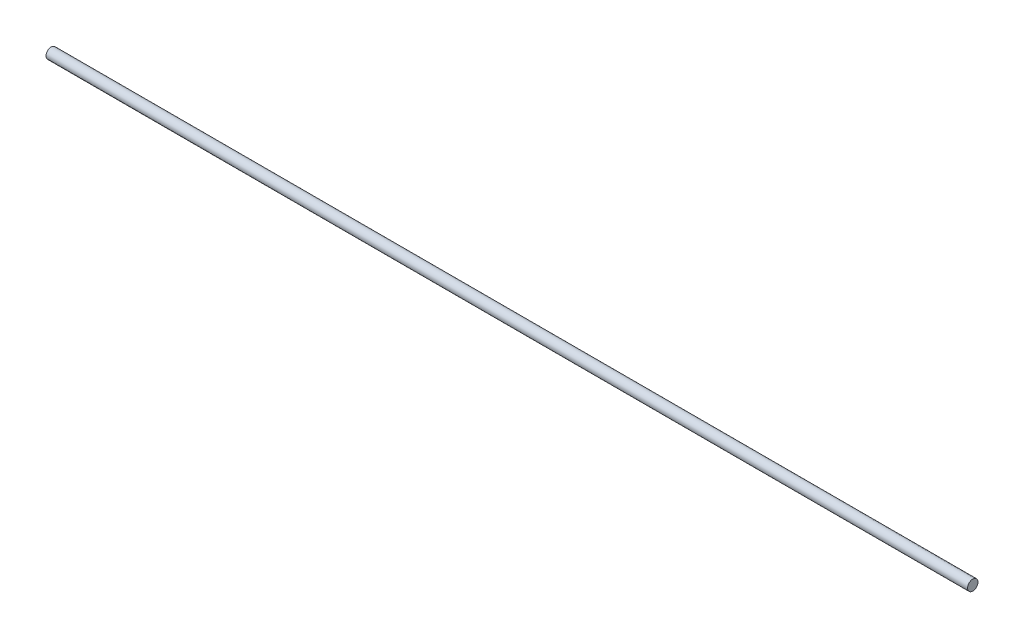
SolidWorks part; units mm, degrees
material "6061-T6 (SS)"
ref_plane "Front Plane" through (0, 0, 0) normal (0, 0, 1) x (1, 0, 0)
ref_plane "Top Plane" through (0, 0, 0) normal (0, 1, 0) x (1, 0, 0)
ref_plane "Right Plane" through (0, 0, 0) normal (1, 0, 0) x (0, 0, -1)
sketch "Sketch1" plane through (0, 0, 0) normal (1, 0, 0) x (0, 0, -1)
  circle A0 centre (0, 0) radius 6.35
  dimension "D1" = 12.7
extrude "Boss-Extrude1" add sketch "Sketch1" along normal blind 1122.172
equation "\"d\"= .5"
equation "\"A\"= 3.14159 * ( \"d\" / 2 ) ^ 2"
equation "\"F\"= 400"
equation "\"E\"= 10 * 10 ^ 6"
equation "\"defl\"= .009"
equation "\"L\"= \"A\" * \"E\" * \"defl\" / \"F\""
equation "\"D1@Boss-Extrude1\"=\"L\""
equation "\"D1@Sketch1\"=\"d\""
